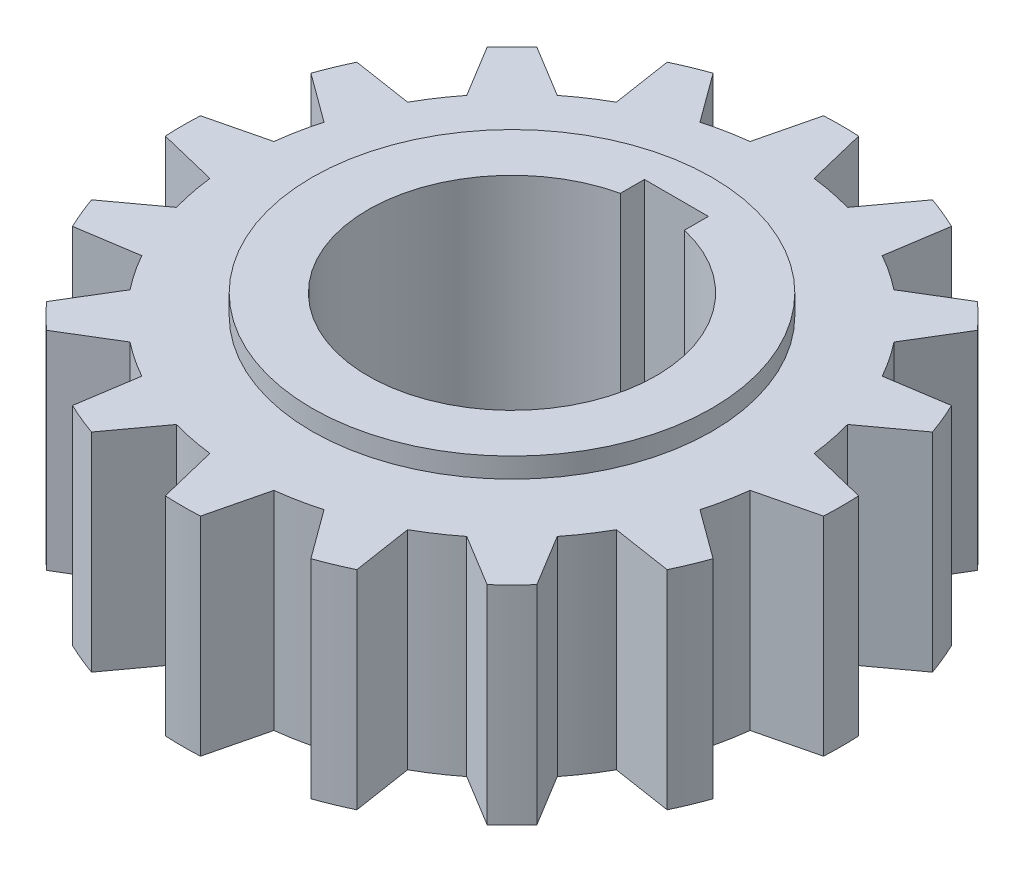
SolidWorks part; units mm, degrees
ref_plane "Front Plane" through (0, 0, 0) normal (0, 0, 1) x (1, 0, 0)
ref_plane "Top Plane" through (0, 0, 0) normal (0, 1, 0) x (1, 0, 0)
ref_plane "Right Plane" through (0, 0, 0) normal (1, 0, 0) x (0, 0, -1)
sketch "Sketch1" plane through (0, 0, 0) normal (0, 1, 0) x (1, 0, 0)
  circle A0 centre (0, 0) radius 105
extrude "Boss-Extrude1" add sketch "Sketch1" along normal mid plane 65
sketch "Sketch2" plane through (0, 0, 0) normal (0, 1, 0) x (1, 0, 0)
  circle A0 centre (0, 0) radius 62.5
extrude "Boss-Extrude2" add sketch "Sketch2" along normal mid plane 77.5
sketch "Sketch3" plane through (0, 38.75, 0) normal (0, 1, 0) x (1, 0, 0)
  line L0 (-10, 43.8748) -> (-10, 51.3748)
  line L1 (-10, 51.3748) -> (10, 51.3748)
  line L2 (10, 51.3748) -> (10, 43.8748)
  line L3 (0, 0) -> (0, 69.5658) construction
  arc A0 (-10, 43.8748) -> (10, 43.8748) centre (0, 0) ccw
  dimension "D1" = 20
  dimension "D4" = 90
  dimension "D2" = 10
  dimension "D3" = 7.5
extrude "Cut-Extrude1" cut sketch "Sketch3" against normal through all
sketch "Sketch4" plane through (0, 32.5, 0) normal (0, 1, 0) x (1, 0, 0)
  line L0 (0, 85) -> (0, 105) construction
  line L1 (-5, 104.8809) -> (-10, 84.4097)
  line L2 (5, 104.8809) -> (10, 84.4097)
  line L3 (35.5168, 98.8107) -> (23.0634, 81.8112)
  line L4 (44.7556, 94.9839) -> (41.541, 74.1576)
  line L5 (70.6265, 77.6975) -> (52.6156, 66.7577)
  line L6 (77.6975, 70.6265) -> (66.7577, 52.6156)
  line L7 (94.9839, 44.7556) -> (74.1576, 41.541)
  line L8 (98.8107, 35.5168) -> (81.8112, 23.0634)
  line L9 (104.8809, 5) -> (84.4097, 10)
  line L10 (104.8809, -5) -> (84.4097, -10)
  line L11 (98.8107, -35.5168) -> (81.8112, -23.0634)
  line L12 (94.9839, -44.7556) -> (74.1576, -41.541)
  line L13 (77.6975, -70.6265) -> (66.7577, -52.6156)
  line L14 (70.6265, -77.6975) -> (52.6156, -66.7577)
  line L15 (44.7556, -94.9839) -> (41.541, -74.1576)
  line L16 (35.5168, -98.8107) -> (23.0634, -81.8112)
  line L17 (5, -104.8809) -> (10, -84.4097)
  line L18 (-5, -104.8809) -> (-10, -84.4097)
  line L19 (-35.5168, -98.8107) -> (-23.0634, -81.8112)
  line L20 (-44.7556, -94.9839) -> (-41.541, -74.1576)
  line L21 (-70.6265, -77.6975) -> (-52.6156, -66.7577)
  line L22 (-77.6975, -70.6265) -> (-66.7577, -52.6156)
  line L23 (-94.9839, -44.7556) -> (-74.1576, -41.541)
  line L24 (-98.8107, -35.5168) -> (-81.8112, -23.0634)
  line L25 (-104.8809, -5) -> (-84.4097, -10)
  line L26 (-104.8809, 5) -> (-84.4097, 10)
  line L27 (-98.8107, 35.5168) -> (-81.8112, 23.0634)
  line L28 (-94.9839, 44.7556) -> (-74.1576, 41.541)
  line L29 (-77.6975, 70.6265) -> (-66.7577, 52.6156)
  line L30 (-70.6265, 77.6975) -> (-52.6156, 66.7577)
  line L31 (-44.7556, 94.9839) -> (-41.541, 74.1576)
  line L32 (-35.5168, 98.8107) -> (-23.0634, 81.8112)
  arc A0 (-44.7556, 94.9839) -> (-70.6265, 77.6975) centre (0, 0) ccw
  arc A1 (-23.0634, -81.8112) -> (-10, -84.4097) centre (0, 0) ccw
  arc A2 (-5, 104.8809) -> (-35.5168, 98.8107) centre (0, 0) ccw
  arc A3 (35.5168, 98.8107) -> (5, 104.8809) centre (0, 0) ccw
  arc A4 (70.6265, 77.6975) -> (44.7556, 94.9839) centre (0, 0) ccw
  arc A5 (-77.6975, 70.6265) -> (-94.9839, 44.7556) centre (0, 0) ccw
  arc A6 (-98.8107, 35.5168) -> (-104.8809, 5) centre (0, 0) ccw
  arc A7 (-104.8809, -5) -> (-98.8107, -35.5168) centre (0, 0) ccw
  arc A8 (-94.9839, -44.7556) -> (-77.6975, -70.6265) centre (0, 0) ccw
  arc A9 (-70.6265, -77.6975) -> (-44.7556, -94.9839) centre (0, 0) ccw
  arc A10 (-35.5168, -98.8107) -> (-5, -104.8809) centre (0, 0) ccw
  arc A11 (-52.6156, -66.7577) -> (-41.541, -74.1576) centre (0, 0) ccw
  arc A12 (-74.1576, -41.541) -> (-66.7577, -52.6156) centre (0, 0) ccw
  arc A13 (-84.4097, -10) -> (-81.8112, -23.0634) centre (0, 0) ccw
  arc A14 (-66.7577, 52.6156) -> (-74.1576, 41.541) centre (0, 0) ccw
  arc A15 (-81.8112, 23.0634) -> (-84.4097, 10) centre (0, 0) ccw
  arc A16 (-41.541, 74.1576) -> (-52.6156, 66.7577) centre (0, 0) ccw
  arc A17 (-10, 84.4097) -> (-23.0634, 81.8112) centre (0, 0) ccw
  arc A18 (23.0634, 81.8112) -> (10, 84.4097) centre (0, 0) ccw
  arc A19 (52.6156, 66.7577) -> (41.541, 74.1576) centre (0, 0) ccw
  arc A20 (74.1576, 41.541) -> (66.7577, 52.6156) centre (0, 0) ccw
  arc A21 (84.4097, 10) -> (81.8112, 23.0634) centre (0, 0) ccw
  arc A22 (81.8112, -23.0634) -> (84.4097, -10) centre (0, 0) ccw
  arc A23 (66.7577, -52.6156) -> (74.1576, -41.541) centre (0, 0) ccw
  arc A24 (41.541, -74.1576) -> (52.6156, -66.7577) centre (0, 0) ccw
  arc A25 (10, -84.4097) -> (23.0634, -81.8112) centre (0, 0) ccw
  arc A26 (5, -104.8809) -> (35.5168, -98.8107) centre (0, 0) ccw
  arc A27 (44.7556, -94.9839) -> (70.6265, -77.6975) centre (0, 0) ccw
  arc A28 (77.6975, -70.6265) -> (94.9839, -44.7556) centre (0, 0) ccw
  arc A29 (98.8107, -35.5168) -> (104.8809, -5) centre (0, 0) ccw
  arc A30 (104.8809, 5) -> (98.8107, 35.5168) centre (0, 0) ccw
  arc A31 (94.9839, 44.7556) -> (77.6975, 70.6265) centre (0, 0) ccw
  point P72 (0, 0)
  dimension "D1" = 170
  dimension "D2" = 210
  dimension "D3" = 5
  dimension "D4" = 5
  dimension "D5" = 10
  dimension "D6" = 10
  dimension "D7" = 16
extrude "Cut-Extrude2" cut sketch "Sketch4" against normal through all
sketch "Sketch5" plane through (0, 32.5, 0) normal (0, 1, 0) x (1, 0, 0)
  circle A0 centre (0, 0) radius 105
  circle A1 centre (0, 0) radius 102.9958
extrude "Cut-Extrude3" cut sketch "Sketch5" against normal through all
